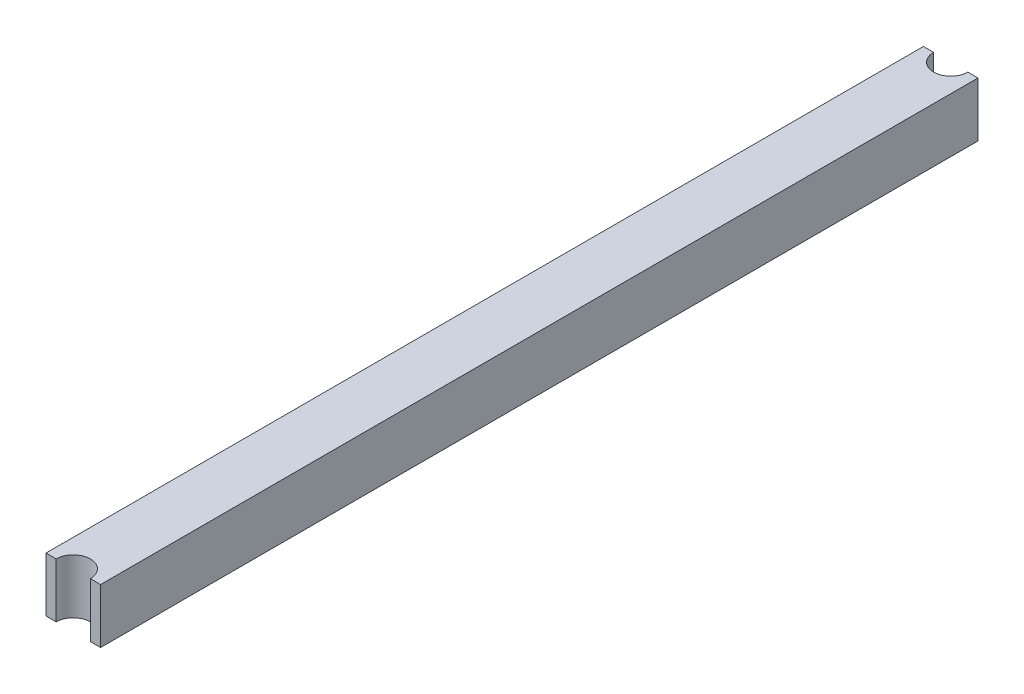
SolidWorks part; units mm, degrees
material "Plain Carbon Steel"
ref_plane "Front Plane" through (0, 0, 0) normal (0, 0, 1) x (1, 0, 0)
ref_plane "Top Plane" through (0, 0, 0) normal (0, 1, 0) x (1, 0, 0)
ref_plane "Right Plane" through (0, 0, 0) normal (1, 0, 0) x (0, 0, -1)
sketch "Sketch1" plane through (0, 0, 0) normal (0, 0, 1) x (1, 0, 0)
  line L1 (-31.1, 31.1) -> (0, 31.1)
  line L2 (-31.1, 31.1) -> (-31.1, 0)
  line L3 (-31.1, 0) -> (0, 0)
  line L4 (0, 31.1) -> (0, 0)
extrude "Boss-Extrude1" add sketch "Sketch1" along normal blind 500
sketch "Sketch2" plane through (0, 31.1, 0) normal (0, 1, 0) x (1, 0, 0)
  line L0 (0, 0) -> (-31.1, 0) construction
  circle A0 centre (-15.55, 0) radius 9.755
  point P4 (0, 0)
  point P5 (-15.55, 0)
extrude "Cut-Extrude1" cut sketch "Sketch2" against normal blind 31.1
sketch "Sketch3" plane through (0, 31.1, 0) normal (0, 1, 0) x (1, 0, 0)
  line L0 (0, -500) -> (-31.1, -500) construction
  circle A0 centre (-15.55, -500) radius 9.755
extrude "Cut-Extrude2" cut sketch "Sketch3" against normal blind 31.1
